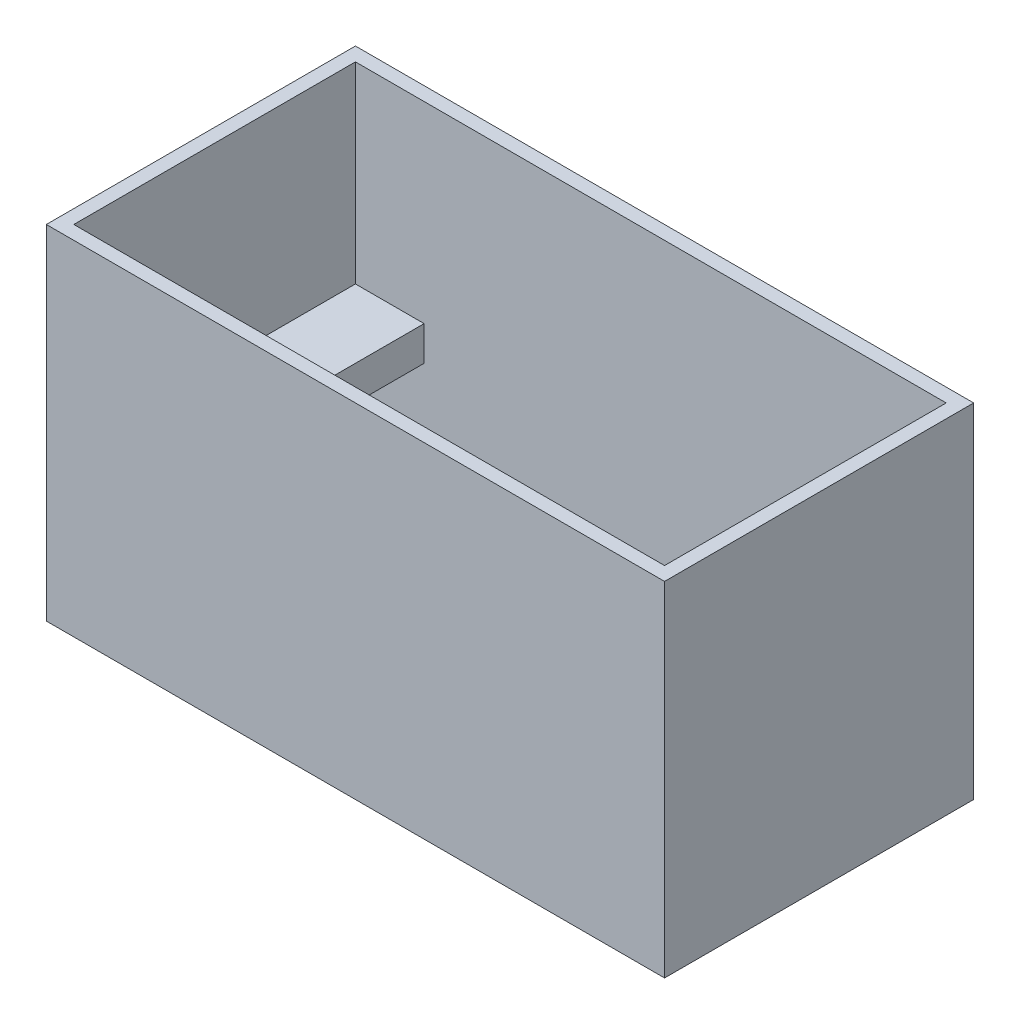
SolidWorks part; units mm, degrees
ref_plane "Front Plane" through (0, 0, 0) normal (0, 0, 1) x (1, 0, 0)
ref_plane "Top Plane" through (0, 0, 0) normal (0, 1, 0) x (1, 0, 0)
ref_plane "Right Plane" through (0, 0, 0) normal (1, 0, 0) x (0, 0, -1)
sketch "Sketch1" plane through (0, 0, 0) normal (0, 1, 0) x (1, 0, 0)
  line L1 (-40.1376, 25.9551) -> (49.8624, 25.9551)
  line L2 (-40.1376, 25.9551) -> (-40.1376, -19.0449)
  line L3 (-40.1376, -19.0449) -> (49.8624, -19.0449)
  line L4 (49.8624, 25.9551) -> (49.8624, -19.0449)
extrude "Boss-Extrude1" add sketch "Sketch1" along normal blind 50
shell "Shell1" thickness 2
sketch "Sketch11" plane through (-38.1376, 0, 0) normal (1, 0, 0) x (0, 0, -1)
  line L1 (-17.0449, 2) -> (23.9551, 2)
  line L2 (-17.0449, 2) -> (-17.0449, 17)
  line L3 (-17.0449, 17) -> (23.9551, 17)
  line L4 (23.9551, 2) -> (23.9551, 17)
sketch "Sketch13" plane through (-38.1376, 0, 0) normal (1, 0, 0) x (0, 0, -1)
  line L1 (-17.0449, 17) -> (24.3617, 17)
  line L2 (-17.0449, 17) -> (-17.0449, 22)
  line L3 (-17.0449, 22) -> (24.3617, 22)
  line L4 (24.3617, 17) -> (24.3617, 22)
extrude "Boss-Extrude3" add sketch "Sketch13" along normal blind 10
sketch "Sketch14" plane through (47.8624, 0, 0) normal (-1, 0, 0) x (0, 0, 1)
  line L1 (17.0449, 2) -> (-23.9551, 2)
  line L2 (17.0449, 2) -> (17.0449, 22)
  line L3 (17.0449, 22) -> (-23.9551, 22)
  line L4 (-23.9551, 2) -> (-23.9551, 22)
sketch "Sketch15" plane through (47.8624, 0, 0) normal (-1, 0, 0) x (0, 0, 1)
  line L1 (17.0449, 22) -> (-23.9551, 22)
  line L2 (17.0449, 22) -> (17.0449, 27)
  line L3 (17.0449, 27) -> (-23.9551, 27)
  line L4 (-23.9551, 22) -> (-23.9551, 27)
extrude "Boss-Extrude4" add sketch "Sketch15" along normal blind 10
extrude "Cut-Extrude1" cut sketch "Sketch11" against normal blind 3
sketch "Sketch18" plane through (0, 27, 0) normal (0, 1, 0) x (1, 0, 0)
  line L1 (47.8624, -17.0449) -> (42.8624, -17.0449)
  line L2 (47.8624, -17.0449) -> (47.8624, 23.9551)
  line L3 (47.8624, 23.9551) -> (42.8624, 23.9551)
  line L4 (42.8624, -17.0449) -> (42.8624, 23.9551)
sketch "Sketch20" plane through (0, 27, 0) normal (0, 1, 0) x (1, 0, 0)
  line L0 (37.8624, -17.0449) -> (37.8624, 23.9551) construction
  line L1 (47.8624, -17.0449) -> (37.8624, -17.0449)
  line L2 (47.8624, -17.0449) -> (47.8624, -12.7949)
  line L3 (47.8624, -12.7949) -> (37.8624, -12.7949)
  line L4 (37.8624, -17.0449) -> (37.8624, -12.7949)
sketch "Sketch22" plane through (0, 27, 0) normal (0, 1, 0) x (1, 0, 0)
  line L1 (37.8624, 23.9551) -> (47.8624, 23.9551)
  line L2 (37.8624, 23.9551) -> (37.8624, 19.7051)
  line L3 (37.8624, 19.7051) -> (47.8624, 19.7051)
  line L4 (47.8624, 23.9551) -> (47.8624, 19.7051)
  line L5 (37.8624, 19.7051) -> (47.8624, 19.7051)
  line L6 (37.8624, 19.7051) -> (37.8624, -12.7949)
  line L7 (37.8624, -12.7949) -> (47.8624, -12.7949)
  line L8 (47.8624, 19.7051) -> (47.8624, -12.7949)
sketch "Sketch24" plane through (0, 27, 0) normal (0, 1, 0) x (1, 0, 0)
  circle A0 centre (42.8958, 16.1852) radius 3.5
sketch "Sketch25" plane through (0, 27, 0) normal (0, 1, 0) x (1, 0, 0)
  circle A0 centre (42.882, -9.3423) radius 3.5
  point P3 (42.882, -9.3423)
sketch "Sketch26" plane through (0, 27, 0) normal (0, 1, 0) x (1, 0, 0)
  circle A0 centre (42.8958, 16.1852) radius 2.5
extrude "Boss-Extrude5" add sketch "Sketch26" along normal blind 10 draft 3
sketch "Sketch27" plane through (0, 27, 0) normal (0, 1, 0) x (1, 0, 0)
  circle A0 centre (42.882, -9.3423) radius 2.5
extrude "Boss-Extrude6" add sketch "Sketch27" along normal blind 10 draft 3
